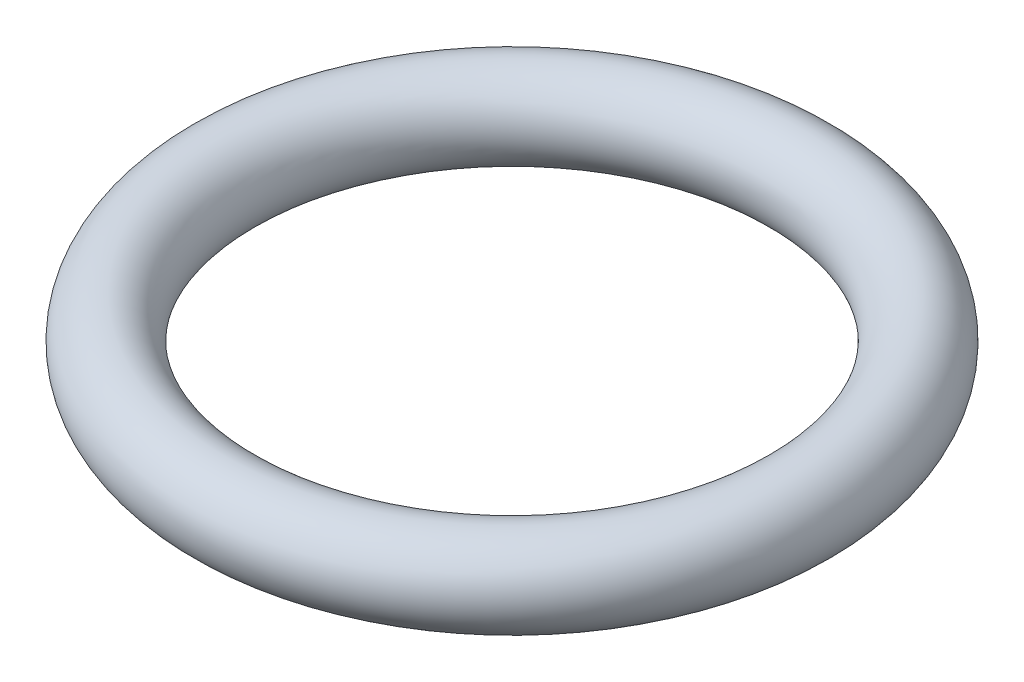
SolidWorks part; units mm, degrees
material "Rubber"
ref_plane "Front Plane" through (0, 0, 0) normal (0, 0, 1) x (1, 0, 0)
ref_plane "Top Plane" through (0, 0, 0) normal (0, 1, 0) x (1, 0, 0)
ref_plane "Right Plane" through (0, 0, 0) normal (1, 0, 0) x (0, 0, -1)
sketch "Sketch1" plane through (0, 0, 0) normal (0, 0, 1) x (1, 0, 0)
  line L0 (0, -48.5698) -> (0, 2379.9192) construction
  circle A0 centre (5.3848, 0) radius 0.7938
  dimension "D1" = 1.5875
  dimension "D2" = 5.3848
revolve "Revolve1" add sketch "Sketch1" angle 360 about L0
